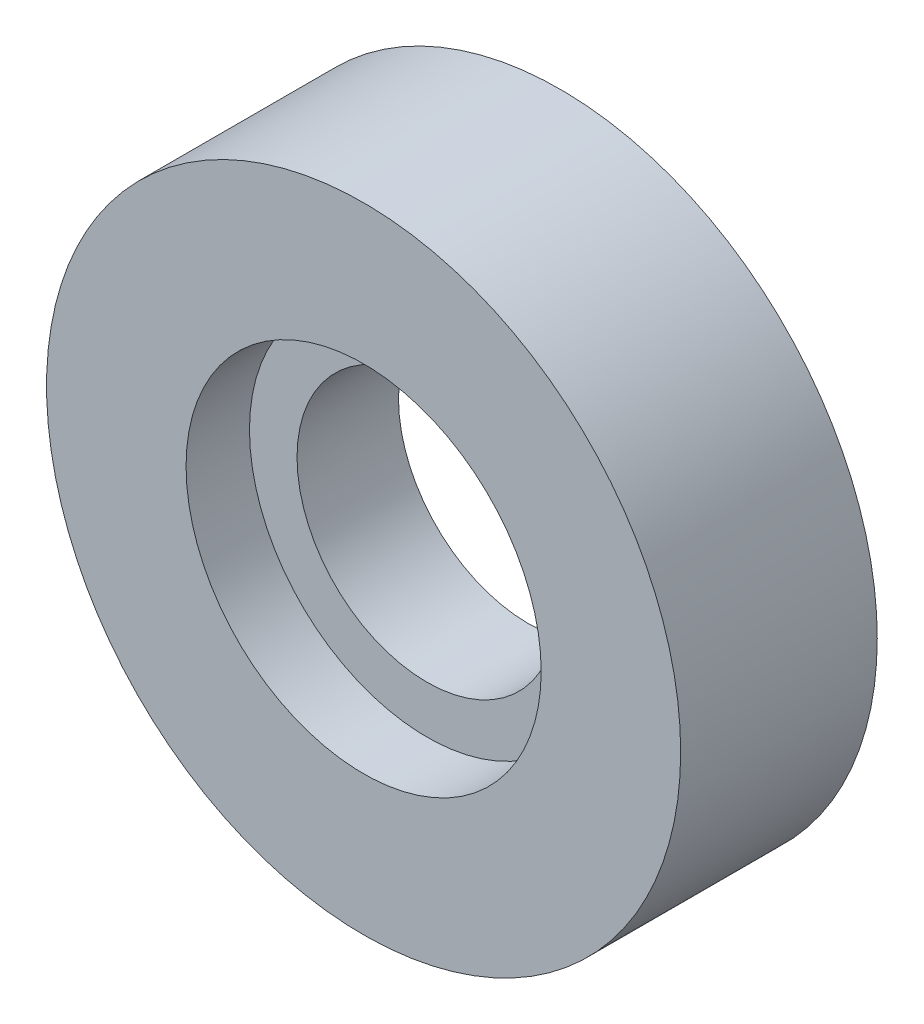
SolidWorks part; units mm, degrees
ref_plane "Front Plane" through (0, 0, 0) normal (0, 0, 1) x (1, 0, 0)
ref_plane "Top Plane" through (0, 0, 0) normal (0, 1, 0) x (1, 0, 0)
ref_plane "Right Plane" through (0, 0, 0) normal (1, 0, 0) x (0, 0, -1)
sketch "Sketch1" plane through (0, 0, 0) normal (1, 0, 0) x (0, 0, -1)
  line L0 (0, 0) -> (80.1603, 0) construction
  line L1 (31, 34) -> (31, 50)
  line L2 (31, 50) -> (0, 50)
  line L5 (10, 28) -> (10, 20.5)
  line L6 (10, 20.5) -> (26, 20.5)
  line L7 (26, 20.5) -> (26, 34)
  line L8 (26, 34) -> (31, 34)
  line L9 (10, 28) -> (0, 28)
  line L10 (0, 28) -> (0, 50)
  dimension "D1" = 68
  dimension "D2" = 100
  dimension "D3" = 5
  dimension "D4" = 10
  dimension "D5" = 41
  dimension "D6" = 56
  dimension "D7" = 31
revolve "Revolve1" add sketch "Sketch1" angle 360 about L0
